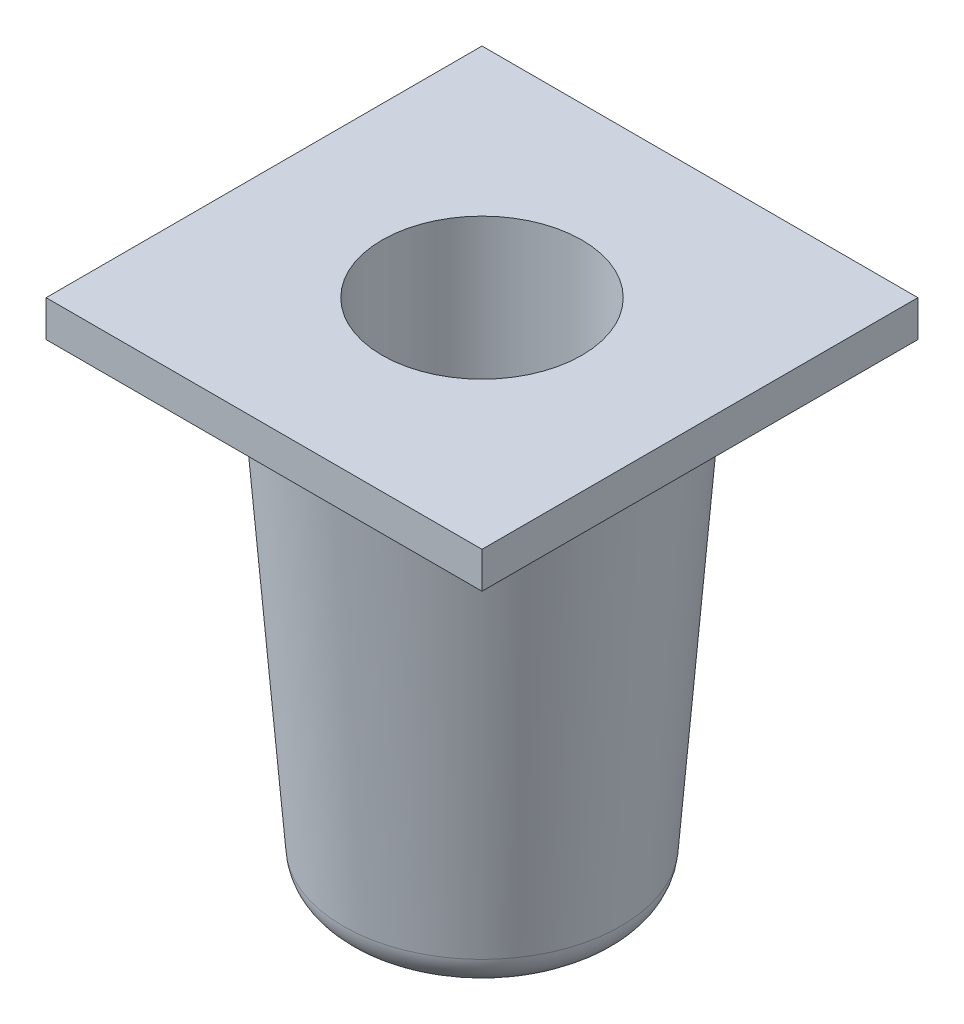
SolidWorks part; units mm, degrees
material "ABS PC"
ref_plane "Piano frontale" through (0, 0, 0) normal (0, 0, 1) x (1, 0, 0)
ref_plane "Piano superiore" through (0, 0, 0) normal (0, 1, 0) x (1, 0, 0)
ref_plane "Piano destro" through (0, 0, 0) normal (1, 0, 0) x (0, 0, -1)
sketch "Schizzo1" plane through (0, 0, 0) normal (0, 1, 0) x (1, 0, 0)
  line L0 (-324.0347, 0) -> (324.0347, 0) construction
  line L2 (-6, -6) -> (6, -6)
  line L3 (-6, -6) -> (-6, 6)
  line L4 (-6, 6) -> (6, 6)
  line L5 (6, -6) -> (6, 6)
  line L6 (-6, -6) -> (6, 6) construction
  line L7 (-6, 6) -> (6, -6) construction
  circle A0 centre (0, 0) radius 2.75
  point P0 (0, 0)
  point P4 (0, 0)
  point P10 (-6, 0)
  dimension "D3" = 5.5
  dimension "D1" = 12
  dimension "D2" = 12
extrude "Estrusione-Estrusione1" add sketch "Schizzo1" along normal blind 1
sketch "Schizzo2" plane through (0, 0, 0) normal (0, 0, 1) x (1, 0, 0)
  line L0 (0, 0) -> (0, -12.3145) construction
  line L1 (-2.75, 0) -> (2.75, 0) construction
  line L2 (-2.75, 0) -> (2.75, 0) construction
  line L5 (3.75, -13) -> (2.75, -13)
  line L6 (2.75, -13) -> (2.75, 0)
  line L7 (2.75, 0) -> (4.7486, 0)
  line L8 (4.7486, 0) -> (3.75, -13)
  line L9 (-6, 0) -> (6, 0) construction
  point P11 (2.75, -4)
  dimension "D1" = 13
  dimension "D2" = 1
  dimension "D3" = 94.393
revolve "Rivoluzione1" add sketch "Schizzo2" angle 360 about L0
fillet "Raccordo1" radius 1 1 edges at (0, -13, 3.75)
